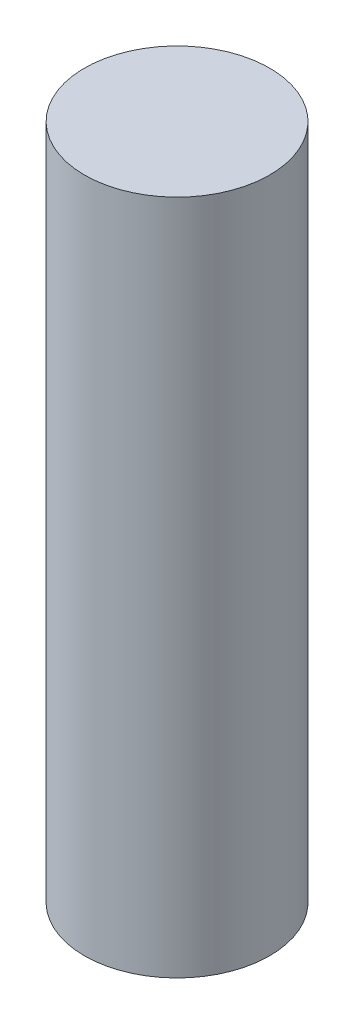
SolidWorks part; units mm, degrees
ref_plane "Plan de face" through (0, 0, 0) normal (0, 0, 1) x (1, 0, 0)
ref_plane "Plan de dessus" through (0, 0, 0) normal (0, 1, 0) x (1, 0, 0)
ref_plane "Plan de droite" through (0, 0, 0) normal (1, 0, 0) x (0, 0, -1)
sketch "Esquisse1" plane through (0, 0, 0) normal (0, 1, 0) x (1, 0, 0)
  circle A0 centre (0, 0) radius 3.15
  dimension "D1" = 6.3
extrude "Boss.-Extru.1" add sketch "Esquisse1" along normal mid plane 23
sketch "Esquisse2" plane through (0, 0, 0) normal (0, 1, 0) x (1, 0, 0)
  point P0 (0, 0)
